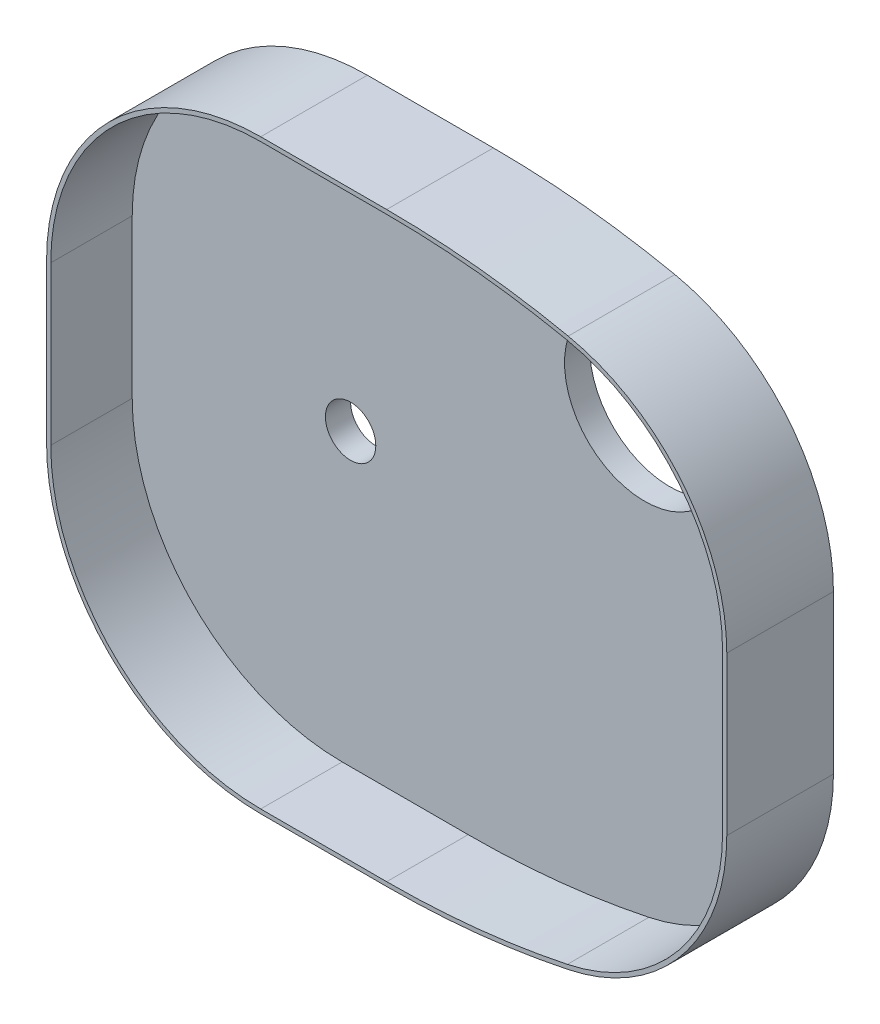
SolidWorks part; units mm, degrees
ref_plane "Front Plane" through (0, 0, 0) normal (0, 0, 1) x (1, 0, 0)
ref_plane "Top Plane" through (0, 0, 0) normal (0, 1, 0) x (1, 0, 0)
ref_plane "Right Plane" through (0, 0, 0) normal (1, 0, 0) x (0, 0, -1)
sketch "Sketch1" plane through (0, 0, 0) normal (0, 0, 1) x (1, 0, 0)
  line L0 (74.9917, 0.3887) -> (74.9917, -2.6113) construction
  line L1 (27.9917, 68.8223) -> (-2.0083, 68.8223)
  line L2 (107.9917, 18.8223) -> (107.9917, -18.8223)
  line L3 (27.9917, -68.8223) -> (-2.0083, -68.8223)
  line L4 (-52.0083, 18.8223) -> (-52.0083, -18.8223)
  line L5 (0, 0) -> (70, 0) construction
  line L6 (70, 0) -> (70, 40) construction
  line L8 (-36.523, 36.9034) -> (31.5065, -36.126) construction
  line L9 (-36.523, -36.126) -> (31.5065, 36.9034) construction
  line L10 (-2.5083, 0.3887) -> (0, 0.3887) construction
  line L11 (0, 0.3887) -> (0, 6.35) construction
  line L12 (0, 0.3887) -> (0, 0) construction
  line L13 (27.9917, 98.8046) -> (27.9917, -68.8223) construction
  line L14 (-52.0083, 0) -> (0, 0) construction
  line L15 (-52.0083, -18.8223) -> (107.9917, -18.8223) construction
  line L16 (31.5065, 36.9034) -> (-36.523, 36.9034) construction
  circle A0 centre (70, 40) radius 19.05
  arc A1 (-2.0083, 68.8223) -> (-52.0083, 18.8223) centre (-2.0083, 18.8223) ccw
  arc A2 (71.0328, 64.3508) -> (27.9917, 68.8223) centre (27.9917, -140.5626) ccw
  arc A3 (107.9917, 18.8223) -> (71.0328, 64.3508) centre (61.4697, 18.8223) ccw
  arc A4 (-2.0083, -68.8223) -> (-52.0083, -18.8223) centre (-2.0083, -18.8223) cw
  arc A5 (71.0328, -64.3508) -> (27.9917, -68.8223) centre (27.9917, 140.5626) cw
  arc A6 (107.9917, -18.8223) -> (71.0328, -64.3508) centre (61.4697, -18.8223) cw
  circle A8 centre (0, 0.3887) radius 6
  dimension "D1" = 38.1
  dimension "D5" = 68.0294
  dimension "D7" = 12
  dimension "D10" = 50
  dimension "D2" = 40
  dimension "D4" = 70
  dimension "D6" = 160
  dimension "D8" = 80
extrude "Boss-Extrude1" add sketch "Sketch1" along normal blind 6
sketch "Sketch2" plane through (0, 0, 0) normal (0, 0, -1) x (-1, 0, 0)
  line L7 (2.0083, 68.8223) -> (-27.9917, 68.8223)
  line L8 (2.0083, 69.8223) -> (-27.9917, 69.8223)
  line L9 (-108.9917, 18.8223) -> (-108.9917, -18.8223)
  line L10 (-27.9917, -69.8223) -> (2.0083, -69.8223)
  line L11 (53.0083, -18.8223) -> (53.0083, 18.8223)
  line L12 (2.0083, 68.8223) -> (-27.9917, 68.8223)
  line L27 (-107.9917, 18.8223) -> (-107.9917, -18.8223)
  line L28 (-27.9917, -68.8223) -> (2.0083, -68.8223)
  line L29 (52.0083, -18.8223) -> (52.0083, 18.8223)
  line L31 (-107.9917, 18.8223) -> (-107.9917, -18.8223)
  line L32 (-27.9917, -68.8223) -> (2.0083, -68.8223)
  line L33 (52.0083, -18.8223) -> (52.0083, 18.8223)
  arc A9 (52.0083, 18.8223) -> (2.0083, 68.8223) centre (2.0083, 18.8223) ccw
  arc A10 (52.0083, 18.8223) -> (2.0083, 68.8223) centre (2.0083, 18.8223) ccw
  arc A11 (-27.9917, 68.8223) -> (-71.0328, 64.3508) centre (-27.9917, -140.5626) ccw
  arc A12 (53.0083, 18.8223) -> (2.0083, 69.8223) centre (2.0083, 18.8223) ccw
  arc A13 (-27.9917, 69.8223) -> (-71.2383, 65.3295) centre (-27.9917, -140.5626) ccw
  arc A14 (-71.2383, 65.3295) -> (-108.9917, 18.8223) centre (-61.4697, 18.8223) ccw
  arc A15 (-108.9917, -18.8223) -> (-71.2383, -65.3295) centre (-61.4697, -18.8223) ccw
  arc A16 (-71.2383, -65.3295) -> (-27.9917, -69.8223) centre (-27.9917, 140.5626) ccw
  arc A17 (2.0083, -69.8223) -> (53.0083, -18.8223) centre (2.0083, -18.8223) ccw
  arc A18 (-27.9917, 68.8223) -> (-71.0328, 64.3508) centre (-27.9917, -140.5626) ccw
  arc A19 (-71.0328, 64.3508) -> (-107.9917, 18.8223) centre (-61.4697, 18.8223) ccw
  arc A20 (-71.0328, 64.3508) -> (-107.9917, 18.8223) centre (-61.4697, 18.8223) ccw
  arc A51 (-107.9917, -18.8223) -> (-71.0328, -64.3508) centre (-61.4697, -18.8223) ccw
  arc A52 (-71.0328, -64.3508) -> (-27.9917, -68.8223) centre (-27.9917, 140.5626) ccw
  arc A53 (2.0083, -68.8223) -> (52.0083, -18.8223) centre (2.0083, -18.8223) ccw
  arc A57 (-107.9917, -18.8223) -> (-71.0328, -64.3508) centre (-61.4697, -18.8223) ccw
  arc A58 (-71.0328, -64.3508) -> (-27.9917, -68.8223) centre (-27.9917, 140.5626) ccw
  arc A59 (2.0083, -68.8223) -> (52.0083, -18.8223) centre (2.0083, -18.8223) ccw
  dimension "D1" = 1
  dimension "D3" = 0
extrude "Boss-Extrude2" add sketch "Sketch2" against normal blind 25.4 separate body
